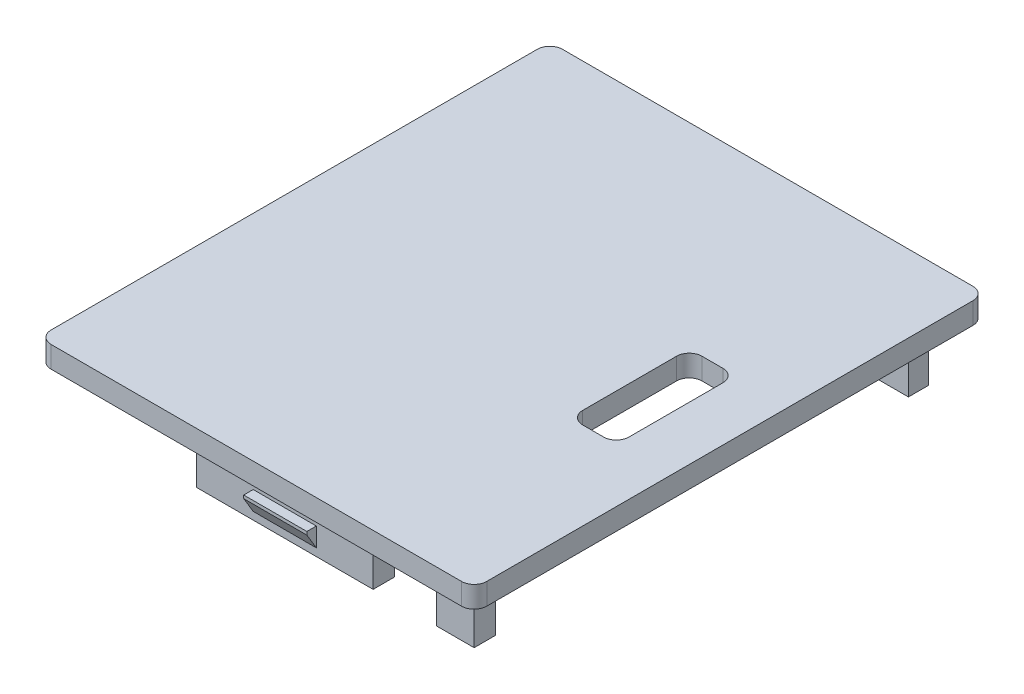
SolidWorks part; units mm, degrees
ref_plane "Front Plane" through (0, 0, 0) normal (0, 0, 1) x (1, 0, 0)
ref_plane "Top Plane" through (0, 0, 0) normal (0, 1, 0) x (1, 0, 0)
ref_plane "Right Plane" through (0, 0, 0) normal (1, 0, 0) x (0, 0, -1)
sketch "Sketch1" plane through (0, 0, 0) normal (0, 1, 0) x (1, 0, 0)
  line L1 (-19.5487, 17.0503) -> (14.9513, 17.0503)
  line L2 (-19.5487, 17.0503) -> (-19.5487, -23.4497)
  line L3 (-19.5487, -23.4497) -> (14.9513, -23.4497)
  line L4 (14.9513, 17.0503) -> (14.9513, -23.4497)
  dimension "D1" = 40.5
  dimension "D2" = 34.5
extrude "Boss-Extrude1" add sketch "Sketch1" along normal blind 1.7 contours L2 L3 L4 L1
sketch "Sketch2" plane through (0, 1.7, 0) normal (0, 1, 0) x (1, 0, 0)
  line L0 (-19.5487, 17.0503) -> (14.9513, 17.0503) construction
  line L1 (-17.2987, 14.8003) -> (12.7013, 14.8003) construction
  line L2 (-17.2987, 14.8003) -> (-17.2987, -21.1997) construction
  line L3 (-17.2987, -21.1997) -> (12.7013, -21.1997) construction
  line L4 (12.7013, 14.8003) -> (12.7013, -21.1997) construction
  line L5 (-19.5487, -23.4497) -> (14.9513, -23.4497) construction
  line L6 (14.9513, 17.0503) -> (14.9513, -23.4497) construction
  line L7 (-19.5487, 17.0503) -> (-19.5487, -23.4497) construction
  line L9 (7.0213, 1.5203) -> (10.6813, 1.5203)
  line L10 (7.0213, 1.5203) -> (7.0213, -7.9197)
  line L11 (7.0213, -7.9197) -> (10.6813, -7.9197)
  line L12 (10.6813, 1.5203) -> (10.6813, -7.9197)
  dimension "D1" = 2.25
  dimension "D2" = 2.25
  dimension "D3" = 2.25
  dimension "D4" = 2.25
  dimension "D5" = 13.28
  dimension "D6" = 13.28
  dimension "D7" = 2.02
  dimension "D8" = 5.68
extrude "Cut-Extrude1" cut sketch "Sketch2" against normal blind 1.7
fillet "Fillet1" radius 1 1 edges at (14.9513, 0.85, 23.4497)
fillet "Fillet2" radius 1 1 edges at (14.9513, 0.85, -17.0503)
fillet "Fillet3" radius 1 1 edges at (-19.5487, 0.85, -17.0503)
fillet "Fillet4" radius 1 1 edges at (-19.5487, 0.85, 23.4497)
fillet "Fillet5" radius 1 1 edges at (7.0213, 0.85, 7.9197)
fillet "Fillet6" radius 1 1 edges at (7.0213, 0.85, -1.5203)
fillet "Fillet7" radius 1 1 edges at (10.6813, 0.85, 7.9197)
fillet "Fillet8" radius 1 1 edges at (10.6813, 0.85, -1.5203)
sketch "Sketch3" plane through (0, 0, 0) normal (0, -1, 0) x (1, 0, 0)
  line L0 (-18.5487, -17.0503) -> (13.9513, -17.0503) construction
  line L1 (12.7013, -13.2003) -> (-17.2987, -13.2003)
  line L2 (12.7013, -13.2003) -> (12.7013, -14.8003)
  line L3 (12.7013, -14.8003) -> (-17.2987, -14.8003)
  line L4 (-17.2987, -13.2003) -> (-17.2987, -14.8003)
  line L5 (14.9513, -16.0503) -> (14.9513, 22.4497) construction
  line L6 (-19.5487, -16.0503) -> (-19.5487, 22.4497) construction
  point P6 (12.7013, -14.0003)
  dimension "D1" = 2.25
  dimension "D2" = 2.25
  dimension "D3" = 2.25
  dimension "D4" = 1.6
extrude "Boss-Extrude2" add sketch "Sketch3" along normal blind 4.6 contours L1 L4 L3 L2
sketch "Sketch4" plane through (0, 0, 0) normal (0, -1, 0) x (1, 0, 0)
  line L0 (14.9513, -16.0503) -> (14.9513, 22.4497) construction
  line L1 (12.7013, 21.1997) -> (9.7013, 21.1997)
  line L2 (12.7013, 21.1997) -> (12.7013, 19.4997)
  line L3 (12.7013, 19.4997) -> (9.7013, 19.4997)
  line L4 (9.7013, 21.1997) -> (9.7013, 19.4997)
  line L5 (-18.5487, 23.4497) -> (13.9513, 23.4497) construction
  line L6 (12.7013, -13.2003) -> (12.7013, -14.8003) construction
  line L7 (12.7013, -13.2003) -> (-17.2987, -13.2003) construction
  line L8 (-19.5487, -16.0503) -> (-19.5487, 22.4497) construction
  line L9 (-9.2987, 21.1997) -> (4.7013, 21.1997)
  line L10 (-9.2987, 21.1997) -> (-9.2987, 19.4997)
  line L11 (-9.2987, 19.4997) -> (4.7013, 19.4997)
  line L12 (4.7013, 21.1997) -> (4.7013, 19.4997)
  point P19 (4.7013, 20.3497)
  dimension "D1" = 2.25
  dimension "D2" = 2.25
  dimension "D3" = 1.7
  dimension "D4" = 3
  dimension "D5" = 2.25
  dimension "D6" = 1.7
  dimension "D7" = 10.25
  dimension "D8" = 10.25
extrude "Boss-Extrude3" add sketch "Sketch4" along normal blind 4.6
sketch "Sketch5" plane through (14.9513, 0, 0) normal (1, 0, 0) x (0, 0, -1)
  line L0 (14.8003, -2.5) -> (14.8003, -4)
  line L1 (14.8003, -4) -> (15.5503, -2.75)
  line L2 (15.5503, -2.75) -> (15.5503, -2.5)
  line L3 (15.5503, -2.5) -> (14.8003, -2.5)
  line L4 (14.8003, -4.6) -> (14.8003, 0) construction
  line L5 (16.0503, 0) -> (-22.4497, 0) construction
  line L6 (-3.1997, 0) -> (-3.1997, 1.7) construction
  line L7 (16.0503, 1.7) -> (-22.4497, 1.7) construction
  line L12 (-21.9497, -2.5) -> (-21.1997, -2.5)
  line L13 (-21.9497, -2.75) -> (-21.9497, -2.5)
  line L14 (-21.1997, -4) -> (-21.9497, -2.75)
  line L15 (-21.1997, -2.5) -> (-21.1997, -4)
  dimension "D1" = 0.75
  dimension "D2" = 0.25
  dimension "D3" = 2.5
  dimension "D4" = 1.5
extrude "Boss-Extrude4" add sketch "Sketch5" against normal offset from surface (5 mm away) 17.5 from offset 14.75 up to face at (12.7013, -2.3, -14.0003) offset against normal yes
fillet "Fillet9" radius 1 1 edges at (11.2013, 0, 19.4997)
fillet "Fillet10" radius 1 1 edges at (-2.2987, 0, 19.4997)
fillet "Fillet11" radius 1 1 edges at (-2.2987, 0, -13.2003)
equation "\"mm\"=17.25"
